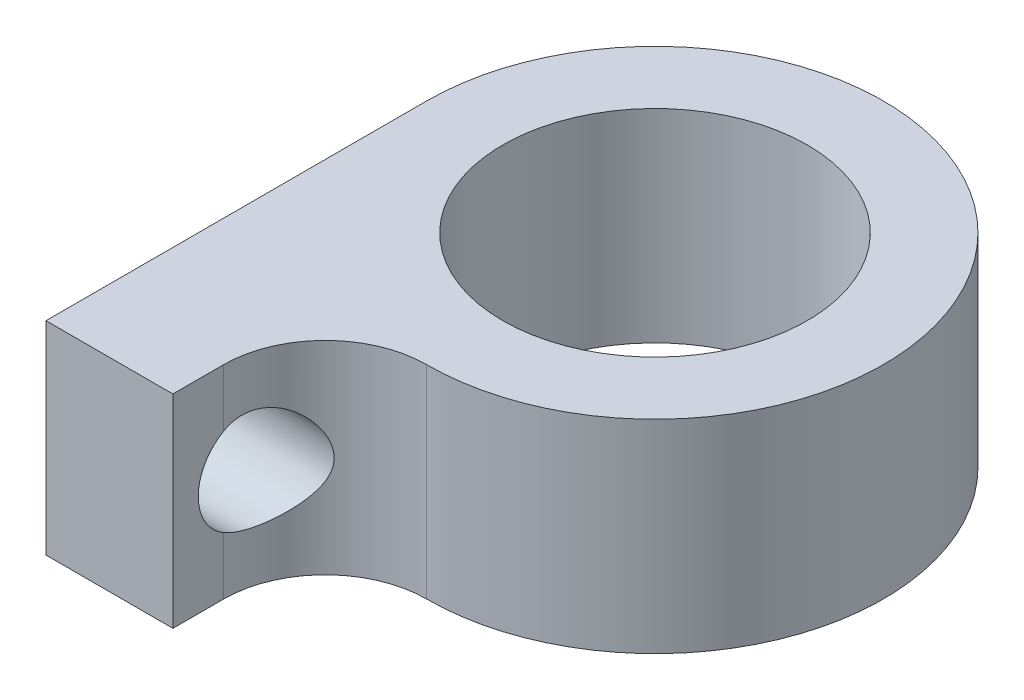
SolidWorks part; units mm, degrees
ref_plane "Alzado" through (0, 0, 0) normal (0, 0, 1) x (1, 0, 0)
ref_plane "Planta" through (0, 0, 0) normal (0, 1, 0) x (1, 0, 0)
ref_plane "Vista lateral" through (0, 0, 0) normal (1, 0, 0) x (0, 0, -1)
sketch "Croquis1" plane through (0, 0, 0) normal (0, 1, 0) x (1, 0, 0)
  line L0 (-9, 0) -> (-9, -15)
  line L1 (-9, -15) -> (-4, -15)
  line L2 (-4, -15) -> (-4, -13)
  line L3 (2.6618, -9) -> (-3.2903, -9) construction
  circle A0 centre (0, 0) radius 6
  arc A1 (0, -9) -> (-9, 0) centre (0, 0) ccw
  arc A2 (0, -9) -> (-4, -13) centre (0, -13) ccw
  dimension "D1" = 12
  dimension "D2" = 3
  dimension "D4" = 4
  dimension "D3" = 15
extrude "Saliente-Extruir1" add sketch "Croquis1" along normal blind 8
sketch "Croquis3" plane through (-9, 0, 0) normal (-1, 0, 0) x (0, 0, 1)
  line L0 (12, 0) -> (12, 8) construction
  line L1 (0, 0) -> (15, 0) construction
  line L2 (0, 8) -> (15, 8) construction
  circle A0 centre (12, 4) radius 2
  dimension "D2" = 4
  dimension "D1" = 3
extrude "Cortar-Extruir1" cut sketch "Croquis3" against normal blind 10
